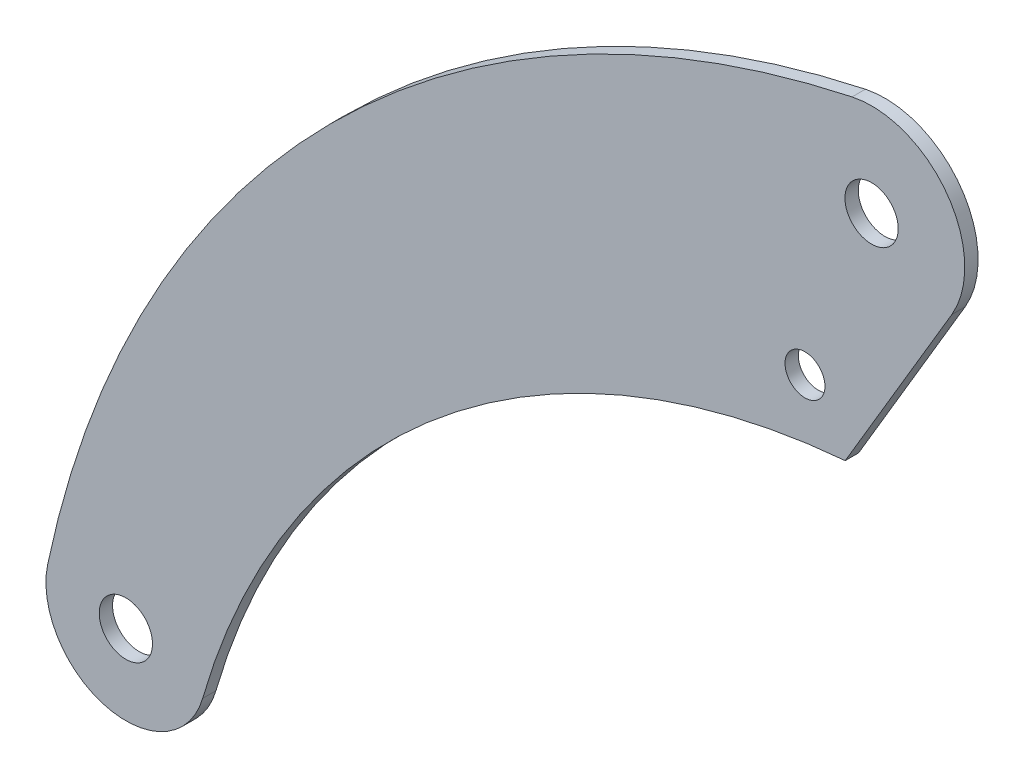
SolidWorks part; units mm, degrees
ref_plane "Front Plane" through (0, 0, 0) normal (0, 0, 1) x (1, 0, 0)
ref_plane "Top Plane" through (0, 0, 0) normal (0, 1, 0) x (1, 0, 0)
ref_plane "Right Plane" through (0, 0, 0) normal (1, 0, 0) x (0, 0, -1)
sketch "Sketch1" plane through (0, 0, 0) normal (0, 0, 1) x (1, 0, 0)
  line L0 (60.2204, -35.6862) -> (-19.7796, -170.6862)
  circle A0 centre (0, 0) radius 20
  circle A1 centre (-50, -130) radius 15
  circle A2 centre (-560, -550) radius 20
  arc A3 (-618.7157, -537.6524) -> (-502.3419, -566.5995) centre (-560, -550) ccw
  arc A4 (-14.6346, 68.4531) -> (60.2204, -35.6862) centre (0, 0) cw
  arc A5 (-19.7796, -170.6862) -> (-502.3419, -566.5995) centre (26.1907, -718.7616) ccw
  arc A6 (-14.6346, 68.4531) -> (-618.7157, -537.6524) centre (149.4818, -699.1997) ccw
  dimension "D1" = 40
  dimension "D2" = 30
  dimension "D3" = 40
  dimension "D8" = 70
  dimension "60" = 60
  dimension "D11" = 550
  dimension "D12" = 785
  dimension "D4" = 50
  dimension "D5" = 130
  dimension "D6" = 560
  dimension "D7" = 550
  dimension "D9" = 135
  dimension "D10" = 80
extrude "Boss-Extrude1" add sketch "Sketch1" along normal mid plane 10
